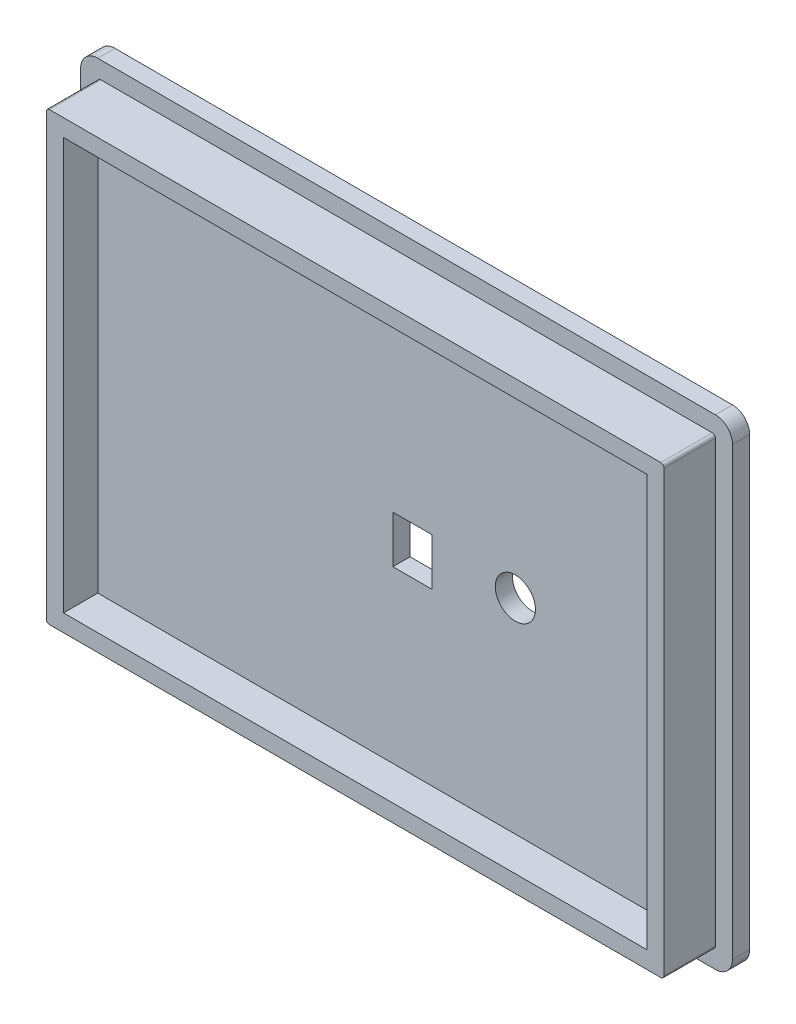
SolidWorks part; units mm, degrees
ref_plane "Front Plane" through (0, 0, 0) normal (0, 0, 1) x (1, 0, 0)
ref_plane "Top Plane" through (0, 0, 0) normal (0, 1, 0) x (1, 0, 0)
ref_plane "Right Plane" through (0, 0, 0) normal (1, 0, 0) x (0, 0, -1)
sketch "Sketch1" plane through (0, 0, 0) normal (0, 0, 1) x (1, 0, 0)
  line L1 (-103.2476, 70.4019) -> (86.7524, 70.4019)
  line L2 (-103.2476, 70.4019) -> (-103.2476, -69.5981)
  line L3 (-103.2476, -69.5981) -> (86.7524, -69.5981)
  line L4 (86.7524, 70.4019) -> (86.7524, -69.5981)
  dimension "D1" = 140
  dimension "D2" = 190
extrude "Boss-Extrude1" add sketch "Sketch1" along normal blind 5
sketch "Sketch2" plane through (0, 0, 0) normal (0, 0, -1) x (-1, 0, 0)
  line L0 (-86.7524, 70.4019) -> (103.2476, 70.4019) construction
  line L1 (-71.7524, 52.4019) -> (88.2476, 52.4019)
  line L2 (-71.7524, 52.4019) -> (-71.7524, -51.5981)
  line L3 (-71.7524, -51.5981) -> (88.2476, -51.5981)
  line L4 (88.2476, 52.4019) -> (88.2476, -51.5981)
  line L5 (-86.7524, -69.5981) -> (-86.7524, 70.4019) construction
  line L6 (103.2476, 70.4019) -> (103.2476, -69.5981) construction
  line L7 (103.2476, -69.5981) -> (-86.7524, -69.5981) construction
  dimension "D1" = 18
  dimension "D2" = 15
  dimension "D3" = 15
  dimension "D4" = 18
extrude "Cut-Extrude1" cut sketch "Sketch2" against normal blind 5
sketch "Sketch3" plane through (0, 0, 5) normal (0, 0, 1) x (1, 0, 0)
  line L0 (86.7524, 70.4019) -> (-103.2476, 70.4019) construction
  line L1 (-98.2476, 65.4019) -> (81.7524, 65.4019)
  line L2 (-98.2476, 65.4019) -> (-98.2476, -64.5981)
  line L3 (-98.2476, -64.5981) -> (81.7524, -64.5981)
  line L4 (81.7524, 65.4019) -> (81.7524, -64.5981)
  line L5 (-103.2476, 70.4019) -> (-103.2476, -69.5981) construction
  line L6 (-103.2476, -69.5981) -> (86.7524, -69.5981) construction
  line L7 (86.7524, -69.5981) -> (86.7524, 70.4019) construction
  dimension "D1" = 5
  dimension "D2" = 5
  dimension "D3" = 5
  dimension "D4" = 5
extrude "Boss-Extrude2" add sketch "Sketch3" along normal blind 15
sketch "Sketch4" plane through (0, 0, 20) normal (0, 0, 1) x (1, 0, 0)
  line L0 (81.7524, 65.4019) -> (-98.2476, 65.4019) construction
  line L1 (-93.2476, 60.4019) -> (76.7524, 60.4019)
  line L2 (-93.2476, 60.4019) -> (-93.2476, -59.5981)
  line L3 (-93.2476, -59.5981) -> (76.7524, -59.5981)
  line L4 (76.7524, 60.4019) -> (76.7524, -59.5981)
  line L5 (-98.2476, 65.4019) -> (-98.2476, -64.5981) construction
  line L6 (-98.2476, -64.5981) -> (81.7524, -64.5981) construction
  line L7 (81.7524, -64.5981) -> (81.7524, 65.4019) construction
  dimension "D1" = 5
  dimension "D2" = 5
  dimension "D3" = 5
  dimension "D4" = 5
extrude "Cut-Extrude2" cut sketch "Sketch4" against normal blind 10
fillet "Fillet1" radius 0.9 4 edges at (71.7524, 0.4019, 0) (-8.2476, -51.5981, 0) (-88.2476, 0.4019, 0) (-8.2476, 52.4019, 0)
fillet "Fillet2" radius 0.9 4 edges at (81.7524, 65.4019, 12.5) (81.7524, -64.5981, 12.5) (-98.2476, 65.4019, 12.5) (-98.2476, -64.5981, 12.5)
sketch "Sketch5" plane through (0, 0, 5) normal (0, 0, -1) x (-1, 0, 0)
  line L1 (-4.2099, 3.8397) -> (7.2345, 3.8397)
  line L2 (-4.2099, 3.8397) -> (-4.2099, -9.9323)
  line L3 (-4.2099, -9.9323) -> (7.2345, -9.9323)
  line L4 (7.2345, 3.8397) -> (7.2345, -9.9323)
  circle A0 centre (-28.4563, 0) radius 5.851
extrude "Cut-Extrude3" cut sketch "Sketch5" against normal blind 10
fillet "Fillet3" radius 5 4 edges at (86.7524, 70.4019, 2.5) (86.7524, -69.5981, 2.5) (-103.2476, -69.5981, 2.5) (-103.2476, 70.4019, 2.5)
